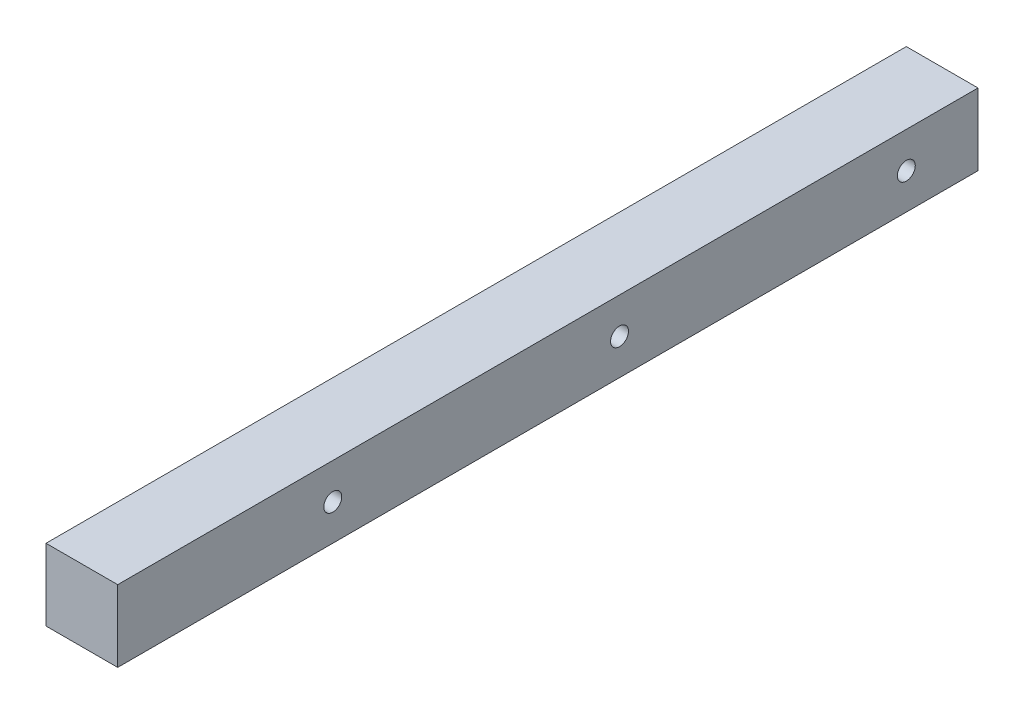
SolidWorks part; units mm, degrees
ref_plane "Front Plane" through (0, 0, 0) normal (0, 0, 1) x (1, 0, 0)
ref_plane "Top Plane" through (0, 0, 0) normal (0, 1, 0) x (1, 0, 0)
ref_plane "Right Plane" through (0, 0, 0) normal (1, 0, 0) x (0, 0, -1)
sketch "Sketch7" plane through (0, 0, 0) normal (0, 0, 1) x (1, 0, 0)
  line L1 (-12.7, -12.7) -> (12.7, -12.7)
  line L2 (-12.7, -12.7) -> (-12.7, 12.7)
  line L3 (-12.7, 12.7) -> (12.7, 12.7)
  line L4 (12.7, -12.7) -> (12.7, 12.7)
  line L5 (-12.7, -12.7) -> (12.7, 12.7) construction
  line L6 (-12.7, 12.7) -> (12.7, -12.7) construction
  point P0 (0, 0)
  dimension "D1" = 25.4
extrude "Boss-Extrude3" add sketch "Sketch7" along normal mid plane 304.8
sketch "Sketch9" plane through (12.7, 0, 0) normal (-1, 0, 0) x (0, -1, 0)
  circle A0 centre (0, -25.4) radius 3.175
  dimension "D1" = 6.35
  dimension "D2" = 25.4
extrude "Cut-Extrude1" cut sketch "Sketch9" along normal through all
pattern_linear "LPattern1" count 2 spacing 101.6 along (0, 0, -1) count 2 spacing 101.6 along (0, 0, 1) of "Cut-Extrude1"
